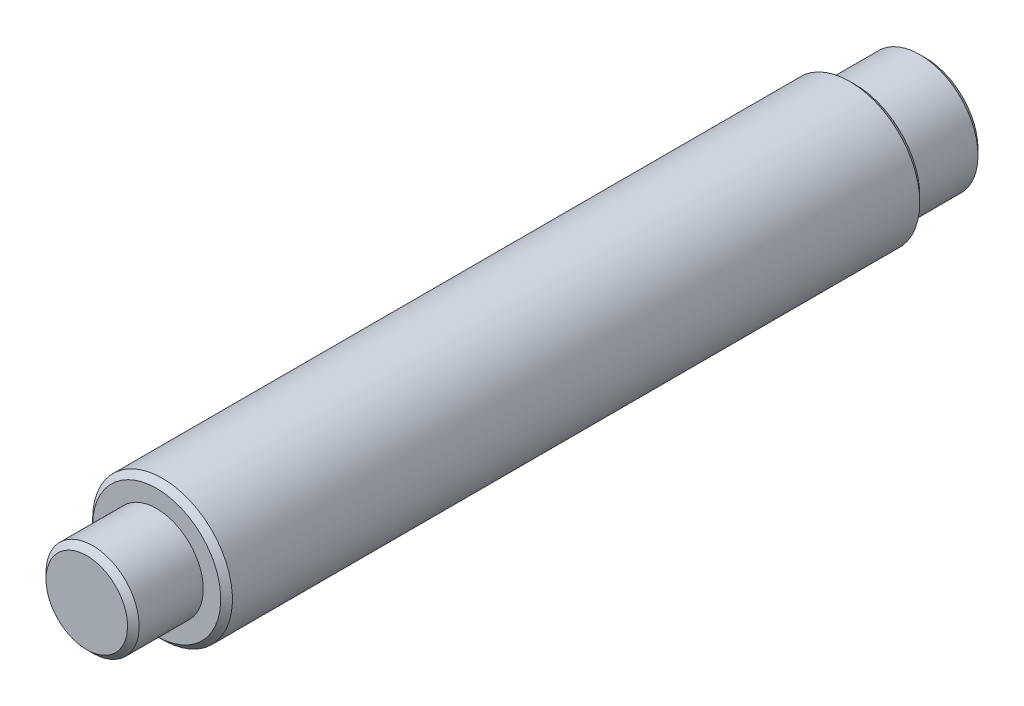
SolidWorks part; units mm, degrees
ref_plane "Plan1" through (0, 0, 0) normal (0, 0, 1) x (1, 0, 0)
ref_plane "Plan2" through (0, 0, 0) normal (0, 1, 0) x (1, 0, 0)
ref_plane "Plan3" through (0, 0, 0) normal (1, 0, 0) x (0, 0, -1)
sketch "Esquisse1" plane through (0, 0, 0) normal (0, 0, 1) x (1, 0, 0)
  circle A0 centre (0, 0) radius 5
  dimension "D1" = 10
extrude "Base-Extrusion" add sketch "Esquisse1" along normal blind 6
sketch "Esquisse2" plane through (0, 0, 6) normal (0, 0, 1) x (1, 0, 0)
  circle A0 centre (0, 0) radius 6
  dimension "D1" = 12
extrude "Boss.-Extru.1" add sketch "Esquisse2" along normal blind 60
sketch "Esquisse3" plane through (0, 0, 66) normal (0, 0, 1) x (1, 0, 0)
  circle A0 centre (0, 0) radius 4
  dimension "D1" = 8
extrude "Boss.-Extru.2" add sketch "Esquisse3" along normal blind 6
chamfer "Chanfrein1" distance 0.5 angle 45
sketch "Esquisse4" plane through (0, 0, 0) normal (0, 1, 0) x (1, 0, 0)
  line L0 (0, -6) -> (0, -0.5) construction
  line L2 (5.5, -6) -> (-5.5, -6) construction
  circle A0 centre (0, -44) radius 2.5
  dimension "D1" = 5
  dimension "D2" = 38
extrude "Enlèv. mat.-Extru.1" cut sketch "Esquisse4" against normal blind 7
